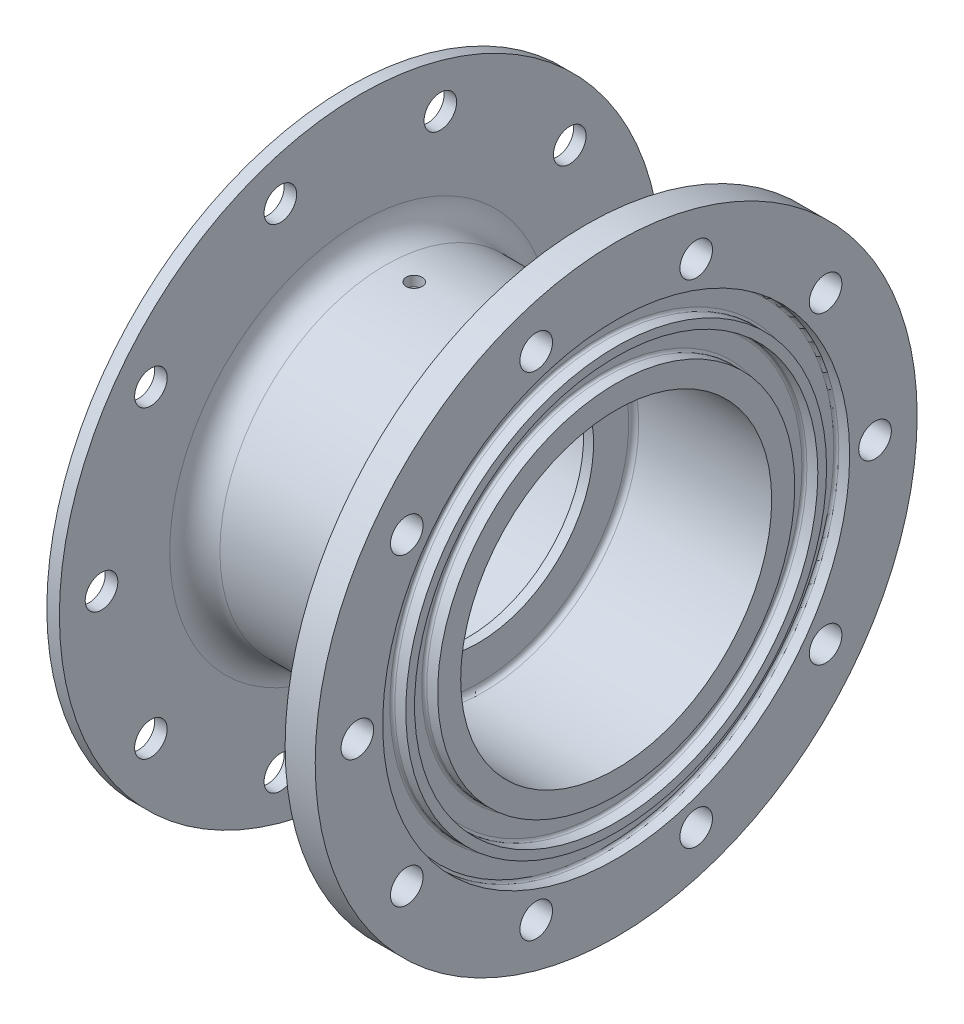
SolidWorks part; units mm, degrees
material "AISI 321 Annealed Stainless Steel (SS)"
ref_plane "Front Plane" through (0, 0, 0) normal (0, 0, 1) x (1, 0, 0)
ref_plane "Top Plane" through (0, 0, 0) normal (0, 1, 0) x (1, 0, 0)
ref_plane "Right Plane" through (0, 0, 0) normal (1, 0, 0) x (0, 0, -1)
sketch "Sketch1" plane through (0, 0, 0) normal (0, 0, 1) x (1, 0, 0)
  line L0 (-117.5079, 0) -> (156.4607, 0) construction
  line L1 (-1, -23) -> (-1, -30)
  line L2 (-11.75, -6.8094) -> (-11.75, -76.6455) construction
  line L3 (1, -23) -> (1, -30)
  line L4 (1, -31) -> (25, -31) construction
  line L5 (25, -31) -> (25, -60) construction
  line L6 (25, -60) -> (22.5, -60)
  line L7 (22.5, -60) -> (22.5, -38)
  line L8 (17.5, -33) -> (-17.5, -33)
  line L9 (-22.5, -38) -> (-22.5, -60)
  line L10 (-22.5, -60) -> (-25, -60)
  line L11 (-25, -60) -> (-25, -31) construction
  line L12 (-25, -31) -> (-1, -31) construction
  line L13 (-1, -23) -> (1, -23)
  line L14 (0, -6.8094) -> (0, -76.6455) construction
  line L15 (-25, -60) -> (-25, -31)
  line L16 (25, -60) -> (25, -31) construction
  line L17 (25, -31) -> (28.5, -31)
  line L18 (28.5, -31) -> (28.5, -60)
  line L19 (-25, -31) -> (-2, -31)
  line L20 (28.5, -60) -> (25, -60)
  line L22 (25, -31) -> (2, -31)
  arc A0 (-22.5, -38) -> (-17.5, -33) centre (-17.5, -38) cw
  arc A1 (22.5, -38) -> (17.5, -33) centre (17.5, -38) ccw
  arc A2 (-1, -30) -> (-2, -31) centre (-2, -30) cw
  arc A3 (2, -31) -> (1, -30) centre (2, -30) cw
  dimension "D5" = 5
  dimension "D6" = 5
  dimension "D9" = 1
  dimension "D10" = 1
  dimension "Inner Radius" = 31
  dimension "D1" = 31
  dimension "Baffle Height" = 8
  dimension "Wall Thickness" = 2
  dimension "Forward Flange Thickness" = 2.5
  dimension "Aft Flange Thickness" = 2.5
  dimension "Baffle Thickness" = 2
  dimension "Catalyst Bed Length" = 50
  dimension "D2" = 24
  dimension "D3" = 1
  dimension "Forward Flange Outer Radius" = 60
  dimension "Aft Flange Outer Radius" = 60
  dimension "D4" = 10.75
  dimension "D7" = 3.5
revolve "Revolve9" add sketch "Sketch1" angle 360 about L0
sketch "Sketch3" plane through (-25, 0, 0) normal (-1, 0, 0) x (0, 0, 1)
  line L0 (0, 0) -> (-15.9453, -49.0745) construction
  line L1 (0, -6.8094) -> (0, -76.6455) construction
  circle A0 centre (-15.9453, -49.0745) radius 3.25
  dimension "D1" = 51.6
  dimension "D2" = 18
  dimension "Forward Flange Hole Diameter" = 6.5
extrude "Cut-Extrude3" cut sketch "Sketch3" against normal through all
pattern_circular "CirPattern1" count 10 over 360 about axis through (0, 0, 0) along (1, 0, 0) of "Cut-Extrude3"
ref_axis "Axis1" through (28.5, 0, 0) along (-1, 0, 0)
hole_wizard "Ø3.2 (3.2) Diameter Hole1" positions "3DSketch1" profile "Sketch7" hole size "Ø3.2" standard "BSI"
sketch3d "3DSketch1"
  line L0 (-11.75, -6.8094, 0) -> (-11.75, -76.6455, 0) construction
  point P0 (-11.75, 33, 0)
sketch "Sketch7" plane through (-11.75, 33, 0) normal (1, 0, 0) x (0, 0, 1)
  line L0 (0, 0) -> (0, 5.9614)
  line L1 (0, 5.9614) -> (1.6, 5)
  line L2 (1.6, 5) -> (1.6, 0)
  line L5 (1.6, 0) -> (0, 0)
  line L10 (0, 5.9614) -> (-1.6, 5) construction
  line L11 (0, -6.35) -> (0, 107.95) construction
  dimension "Hole Dia." = 3.2
  dimension "Hole Depth" = 5
  dimension "Drill Angle" = 118
ref_plane "Plane1" through (-25, 0, 0) normal (0, -1, 0) x (0, 0, 1)
ref_plane "Plane2" through (25, 0, 0) normal (0, -1, 0) x (0, 0, -1)
ref_plane "Plane3" through (25, 0, 0) normal (0, -1, 0) x (0, 0, -1)
ref_plane "Plane4" through (25, 0, 0) normal (0, -1, 0) x (0, 0, -1)
ref_plane "Plane5" through (25, 0, 0) normal (0, -1, 0) x (0, 0, -1)
ref_plane "Plane6" through (25, 0, 0) normal (0, -1, 0) x (0, 0, -1)
sketch "Sketch8" plane through (0, 0, 0) normal (0, 0, 1) x (1, 0, 0)
  line L0 (28.5, -60) -> (28.5, 60) construction
  line L1 (28.5, 40.195) -> (26.33, 40.195)
  line L2 (25.83, 39.695) -> (25.83, 36.095)
  line L3 (26.33, 35.595) -> (28.5, 35.595)
  line L4 (28.5, 35.595) -> (28.5, 40.195)
  line L5 (28.5, 41.945) -> (26.33, 41.945)
  line L6 (25.83, 42.445) -> (25.83, 46.045)
  line L7 (26.33, 46.545) -> (28.5, 46.545)
  line L8 (28.5, 45.8245) -> (28.5, 52.3245) construction
  line L9 (28.5, 46.545) -> (28.5, 41.945)
  arc A0 (25.83, 36.095) -> (26.33, 35.595) centre (26.33, 36.095) ccw
  arc A1 (25.83, 39.695) -> (26.33, 40.195) centre (26.33, 39.695) cw
  arc A2 (25.83, 42.445) -> (26.33, 41.945) centre (26.33, 42.445) ccw
  arc A3 (25.83, 46.045) -> (26.33, 46.545) centre (26.33, 46.045) cw
  point P0 (28.5, 37.895)
  point P1 (28.5, 44.245)
  point P17 (25.83, 35.595)
  point P20 (25.83, 40.195)
  point P25 (25.83, 46.545)
  dimension "D9" = 0.5
  dimension "D10" = 0.5
  dimension "D11" = 0.5
  dimension "D12" = 0.5
  dimension "D1" = 37.895
  dimension "D2" = 44.245
  dimension "D3" = 4.6
  dimension "D4" = 2.3
  dimension "D5" = 2.67
  dimension "D6" = 2.67
  dimension "D7" = 4.6
  dimension "D8" = 2.3
revolve "Cut-Revolve1" cut sketch "Sketch8" angle 360 about axis through (28.5, 0, 0) along (-1, 0, 0)
equation "\"D1@Sketch1\"=\"Inner Radius@Sketch1\""
equation "\"D2@Sketch1\"=(\"Catalyst Bed Length@Sketch1\"/2)-(\"Baffle Thickness@Sketch1\"/2)"
equation "\"D3@Sketch1\"=\"Baffle Thickness@Sketch1\"/2"
equation "\"Aft Flange Outer Radius@Sketch1\"=\"Forward Flange Outer Radius@Sketch1\""
equation "\"D1@Cut-Extrude3\"=\"Forward Flange Thickness@Sketch1\""
equation "\"D4@Sketch1\"=21.5/2"
equation "\"D7@Sketch1\"=6-2.5"
equation "\"D1@Sketch8\"=75.79/2"
equation "\"D2@Sketch8\"=88.49/2"
